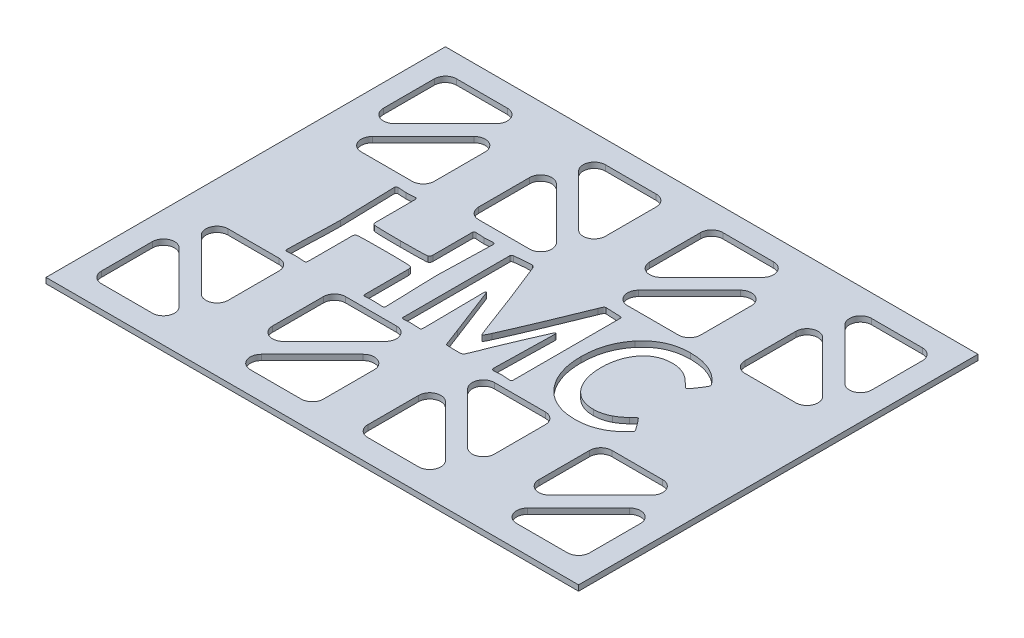
SolidWorks part; units mm, degrees
material "1060 Alloy"
ref_plane "Front Plane" through (0, 0, 0) normal (0, 0, 1) x (1, 0, 0)
ref_plane "Top Plane" through (0, 0, 0) normal (0, 1, 0) x (1, 0, 0)
ref_plane "Right Plane" through (0, 0, 0) normal (1, 0, 0) x (0, 0, -1)
sketch "Sketch2" plane through (0, 0, 0) normal (0, 1, 0) x (1, 0, 0)
  line L0 (-240.3287, 78.4637) -> (-240.3287, 20.2243)
  line L1 (-265.7287, 116.5637) -> (343.8713, 116.5637)
  line L2 (-265.7287, 116.5637) -> (-265.7287, -340.6363)
  line L3 (-265.7287, -340.6363) -> (343.8713, -340.6363)
  line L4 (343.8713, 116.5637) -> (343.8713, -340.6363)
  line L5 (-218.6484, 11.244) -> (-160.4089, 69.4835)
  line L6 (-169.3892, 91.1637) -> (-227.6287, 91.1637)
  line L7 (-218.6484, -14.156) -> (-160.4089, 44.0835)
  line L8 (-138.7287, 35.1032) -> (-138.7287, -23.1363)
  line L9 (-151.4287, -35.8363) -> (-209.6682, -35.8363)
  line L10 (39.0713, 116.5637) -> (39.0713, -340.6363) construction
  line L11 (343.8713, -112.0363) -> (-265.7287, -112.0363) construction
  line L12 (-113.3287, 116.5637) -> (-113.3287, -340.6363) construction
  line L13 (-75.2287, -35.8363) -> (-16.9892, -35.8363)
  line L14 (-87.9287, 35.1032) -> (-87.9287, -23.1363)
  line L15 (-8.0089, -14.156) -> (-66.2484, 44.0835)
  line L16 (-57.2682, 91.1637) -> (0.9713, 91.1637)
  line L17 (-8.0089, 11.244) -> (-66.2484, 69.4835)
  line L18 (13.6713, 78.4637) -> (13.6713, 20.2243)
  line L19 (64.4713, 78.4637) -> (64.4713, 20.2243)
  line L20 (86.1516, 11.244) -> (144.3911, 69.4835)
  line L21 (135.4108, 91.1637) -> (77.1713, 91.1637)
  line L22 (86.1516, -14.156) -> (144.3911, 44.0835)
  line L23 (166.0713, 35.1032) -> (166.0713, -23.1363)
  line L24 (153.3713, -35.8363) -> (95.1318, -35.8363)
  line L25 (229.5713, -35.8363) -> (287.8108, -35.8363)
  line L26 (216.8713, 35.1032) -> (216.8713, -23.1363)
  line L27 (296.7911, -14.156) -> (238.5516, 44.0835)
  line L28 (247.5318, 91.1637) -> (305.7713, 91.1637)
  line L29 (296.7911, 11.244) -> (238.5516, 69.4835)
  line L30 (318.4713, 78.4637) -> (318.4713, 20.2243)
  line L31 (318.4713, -302.5363) -> (318.4713, -244.2968)
  line L32 (296.7911, -235.3165) -> (238.5516, -293.556)
  line L33 (247.5318, -315.2363) -> (305.7713, -315.2363)
  line L34 (296.7911, -209.9165) -> (238.5516, -268.156)
  line L35 (216.8713, -259.1757) -> (216.8713, -200.9363)
  line L36 (229.5713, -188.2363) -> (287.8108, -188.2363)
  line L37 (153.3713, -188.2363) -> (95.1318, -188.2363)
  line L38 (166.0713, -259.1757) -> (166.0713, -200.9363)
  line L39 (86.1516, -209.9165) -> (144.3911, -268.156)
  line L40 (135.4108, -315.2363) -> (77.1713, -315.2363)
  line L41 (86.1516, -235.3165) -> (144.3911, -293.556)
  line L42 (64.4713, -302.5363) -> (64.4713, -244.2968)
  line L43 (13.6713, -302.5363) -> (13.6713, -244.2968)
  line L44 (-8.0089, -235.3165) -> (-66.2484, -293.556)
  line L45 (-57.2682, -315.2363) -> (0.9713, -315.2363)
  line L46 (-8.0089, -209.9165) -> (-66.2484, -268.156)
  line L47 (-87.9287, -259.1757) -> (-87.9287, -200.9363)
  line L48 (-75.2287, -188.2363) -> (-16.9892, -188.2363)
  line L49 (-151.4287, -188.2363) -> (-209.6682, -188.2363)
  line L50 (-138.7287, -259.1757) -> (-138.7287, -200.9363)
  line L51 (-218.6484, -209.9165) -> (-160.4089, -268.156)
  line L52 (-169.3892, -315.2363) -> (-227.6287, -315.2363)
  line L53 (-218.6484, -235.3165) -> (-160.4089, -293.556)
  line L54 (-240.3287, -302.5363) -> (-240.3287, -244.2968)
  arc A0 (-160.4089, 44.0835) -> (-138.7287, 35.1032) centre (-151.4287, 35.1032) cw
  arc A1 (-138.7287, -23.1363) -> (-151.4287, -35.8363) centre (-151.4287, -23.1363) cw
  arc A2 (-218.6484, -14.156) -> (-209.6682, -35.8363) centre (-209.6682, -23.1363) ccw
  arc A3 (-240.3287, 20.2243) -> (-218.6484, 11.244) centre (-227.6287, 20.2243) ccw
  arc A4 (-160.4089, 69.4835) -> (-169.3892, 91.1637) centre (-169.3892, 78.4637) ccw
  arc A5 (-240.3287, 78.4637) -> (-227.6287, 91.1637) centre (-227.6287, 78.4637) cw
  arc A6 (13.6713, 78.4637) -> (0.9713, 91.1637) centre (0.9713, 78.4637) ccw
  arc A7 (-66.2484, 69.4835) -> (-57.2682, 91.1637) centre (-57.2682, 78.4637) cw
  arc A8 (13.6713, 20.2243) -> (-8.0089, 11.244) centre (0.9713, 20.2243) cw
  arc A9 (-8.0089, -14.156) -> (-16.9892, -35.8363) centre (-16.9892, -23.1363) cw
  arc A10 (-87.9287, -23.1363) -> (-75.2287, -35.8363) centre (-75.2287, -23.1363) ccw
  arc A11 (-66.2484, 44.0835) -> (-87.9287, 35.1032) centre (-75.2287, 35.1032) ccw
  arc A12 (144.3911, 44.0835) -> (166.0713, 35.1032) centre (153.3713, 35.1032) cw
  arc A13 (166.0713, -23.1363) -> (153.3713, -35.8363) centre (153.3713, -23.1363) cw
  arc A14 (86.1516, -14.156) -> (95.1318, -35.8363) centre (95.1318, -23.1363) ccw
  arc A15 (64.4713, 20.2243) -> (86.1516, 11.244) centre (77.1713, 20.2243) ccw
  arc A16 (144.3911, 69.4835) -> (135.4108, 91.1637) centre (135.4108, 78.4637) ccw
  arc A17 (64.4713, 78.4637) -> (77.1713, 91.1637) centre (77.1713, 78.4637) cw
  arc A18 (318.4713, 78.4637) -> (305.7713, 91.1637) centre (305.7713, 78.4637) ccw
  arc A19 (238.5516, 69.4835) -> (247.5318, 91.1637) centre (247.5318, 78.4637) cw
  arc A20 (318.4713, 20.2243) -> (296.7911, 11.244) centre (305.7713, 20.2243) cw
  arc A21 (296.7911, -14.156) -> (287.8108, -35.8363) centre (287.8108, -23.1363) cw
  arc A22 (216.8713, -23.1363) -> (229.5713, -35.8363) centre (229.5713, -23.1363) ccw
  arc A23 (238.5516, 44.0835) -> (216.8713, 35.1032) centre (229.5713, 35.1032) ccw
  arc A24 (238.5516, -268.156) -> (216.8713, -259.1757) centre (229.5713, -259.1757) cw
  arc A25 (216.8713, -200.9363) -> (229.5713, -188.2363) centre (229.5713, -200.9363) cw
  arc A26 (296.7911, -209.9165) -> (287.8108, -188.2363) centre (287.8108, -200.9363) ccw
  arc A27 (318.4713, -244.2968) -> (296.7911, -235.3165) centre (305.7713, -244.2968) ccw
  arc A28 (238.5516, -293.556) -> (247.5318, -315.2363) centre (247.5318, -302.5363) ccw
  arc A29 (318.4713, -302.5363) -> (305.7713, -315.2363) centre (305.7713, -302.5363) cw
  arc A30 (64.4713, -302.5363) -> (77.1713, -315.2363) centre (77.1713, -302.5363) ccw
  arc A31 (144.3911, -293.556) -> (135.4108, -315.2363) centre (135.4108, -302.5363) cw
  arc A32 (64.4713, -244.2968) -> (86.1516, -235.3165) centre (77.1713, -244.2968) cw
  arc A33 (86.1516, -209.9165) -> (95.1318, -188.2363) centre (95.1318, -200.9363) cw
  arc A34 (166.0713, -200.9363) -> (153.3713, -188.2363) centre (153.3713, -200.9363) ccw
  arc A35 (144.3911, -268.156) -> (166.0713, -259.1757) centre (153.3713, -259.1757) ccw
  arc A36 (-66.2484, -268.156) -> (-87.9287, -259.1757) centre (-75.2287, -259.1757) cw
  arc A37 (-87.9287, -200.9363) -> (-75.2287, -188.2363) centre (-75.2287, -200.9363) cw
  arc A38 (-8.0089, -209.9165) -> (-16.9892, -188.2363) centre (-16.9892, -200.9363) ccw
  arc A39 (13.6713, -244.2968) -> (-8.0089, -235.3165) centre (0.9713, -244.2968) ccw
  arc A40 (-66.2484, -293.556) -> (-57.2682, -315.2363) centre (-57.2682, -302.5363) ccw
  arc A41 (13.6713, -302.5363) -> (0.9713, -315.2363) centre (0.9713, -302.5363) cw
  arc A42 (-240.3287, -302.5363) -> (-227.6287, -315.2363) centre (-227.6287, -302.5363) ccw
  arc A43 (-160.4089, -293.556) -> (-169.3892, -315.2363) centre (-169.3892, -302.5363) cw
  arc A44 (-240.3287, -244.2968) -> (-218.6484, -235.3165) centre (-227.6287, -244.2968) cw
  arc A45 (-218.6484, -209.9165) -> (-209.6682, -188.2363) centre (-209.6682, -200.9363) cw
  arc A46 (-138.7287, -200.9363) -> (-151.4287, -188.2363) centre (-151.4287, -200.9363) ccw
  arc A47 (-160.4089, -268.156) -> (-138.7287, -259.1757) centre (-151.4287, -259.1757) ccw
  text T0 "HMC" font "Berlin Sans FB" height 127
  point P19 (-138.7287, 65.7637)
  point P22 (-138.7287, -35.8363)
  point P25 (-240.3287, -35.8363)
  point P28 (-240.3287, -10.4363)
  point P31 (-138.7287, 91.1637)
  point P34 (-240.3287, 91.1637)
  point P53 (13.6713, 91.1637)
  point P54 (-87.9287, 91.1637)
  point P55 (13.6713, -10.4363)
  point P56 (13.6713, -35.8363)
  point P57 (-87.9287, -35.8363)
  point P58 (-87.9287, 65.7637)
  point P95 (166.0713, 65.7637)
  point P96 (166.0713, -35.8363)
  point P97 (64.4713, -35.8363)
  point P98 (64.4713, -10.4363)
  point P99 (166.0713, 91.1637)
  point P100 (64.4713, 91.1637)
  point P101 (318.4713, 91.1637)
  point P102 (216.8713, 91.1637)
  point P103 (318.4713, -10.4363)
  point P104 (318.4713, -35.8363)
  point P105 (216.8713, -35.8363)
  point P106 (216.8713, 65.7637)
  point P179 (216.8713, -289.8363)
  point P180 (216.8713, -188.2363)
  point P181 (318.4713, -188.2363)
  point P182 (318.4713, -213.6363)
  point P183 (216.8713, -315.2363)
  point P184 (318.4713, -315.2363)
  point P185 (64.4713, -315.2363)
  point P186 (166.0713, -315.2363)
  point P187 (64.4713, -213.6363)
  point P188 (64.4713, -188.2363)
  point P189 (166.0713, -188.2363)
  point P190 (166.0713, -289.8363)
  point P191 (-87.9287, -289.8363)
  point P192 (-87.9287, -188.2363)
  point P193 (13.6713, -188.2363)
  point P194 (13.6713, -213.6363)
  point P195 (-87.9287, -315.2363)
  point P196 (13.6713, -315.2363)
  point P197 (-240.3287, -315.2363)
  point P198 (-138.7287, -315.2363)
  point P199 (-240.3287, -213.6363)
  point P200 (-240.3287, -188.2363)
  point P201 (-138.7287, -188.2363)
  point P202 (-138.7287, -289.8363)
  dimension "D11" = 12.7
  dimension "D1" = 609.6
  dimension "D2" = 457.2
  dimension "D3" = 25.4
  dimension "D4" = 25.4
  dimension "D5" = 101.6
  dimension "D6" = 101.6
  dimension "D7" = 101.6
  dimension "D8" = 101.6
  dimension "D9" = 25.4
  dimension "D10" = 152.4
extrude "Boss-Extrude1" add sketch "Sketch2" along normal blind 6.35
